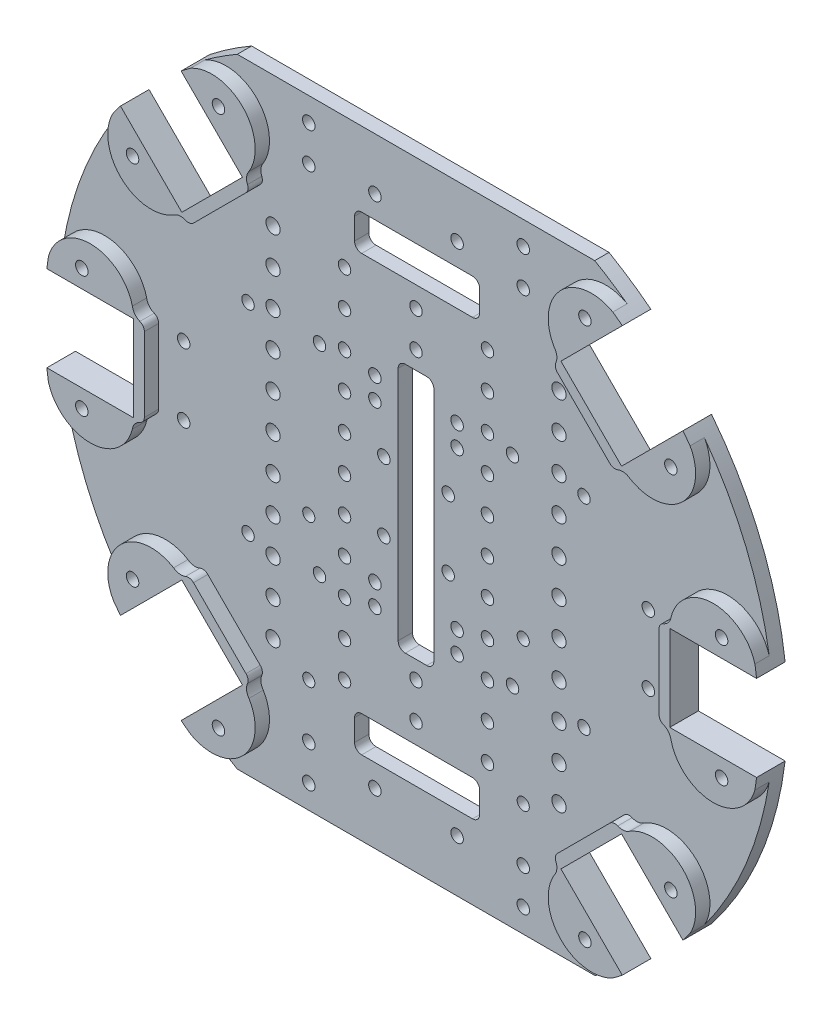
SolidWorks part; units mm, degrees
ref_plane "Front Plane" through (0, 0, 0) normal (0, 0, 1) x (1, 0, 0)
ref_plane "Top Plane" through (0, 0, 0) normal (0, 1, 0) x (1, 0, 0)
ref_plane "Right Plane" through (0, 0, 0) normal (1, 0, 0) x (0, 0, -1)
sketch "Sketch1" plane through (0, 0, 0) normal (0, 0, 1) x (1, 0, 0)
  line L0 (0, 0) -> (0, 100) construction
  line L5 (44.5477, 61.5183) -> (61.7144, 78.685)
  line L6 (44.5477, 61.5183) -> (61.5183, 44.5477)
  line L7 (-12, 75) -> (12, 75) construction
  line L8 (-12, 75) -> (-12, 99.2774) construction
  line L9 (12, 75) -> (12, 99.2774) construction
  line L10 (-17, 89.5) -> (17, 89.5) construction
  line L11 (61.5183, 44.5477) -> (78.685, 61.7144)
  line L12 (75, 12) -> (99.2774, 12)
  line L13 (75, 12) -> (75, -12)
  line L14 (75, -12) -> (99.2774, -12)
  line L15 (61.5183, -44.5477) -> (78.685, -61.7144)
  line L16 (61.5183, -44.5477) -> (44.5477, -61.5183)
  line L17 (44.5477, -61.5183) -> (61.7144, -78.685)
  line L18 (12, -75) -> (12, -99.2774) construction
  line L19 (12, -75) -> (-12, -75) construction
  line L20 (-12, -75) -> (-12, -99.2774) construction
  line L21 (-44.5477, -61.5183) -> (-61.7144, -78.685)
  line L22 (-44.5477, -61.5183) -> (-61.5183, -44.5477)
  line L23 (-61.5183, -44.5477) -> (-78.685, -61.7144)
  line L24 (-75, -12) -> (-99.2774, -12)
  line L25 (-75, -12) -> (-75, 12)
  line L26 (-75, 12) -> (-99.2774, 12)
  line L27 (-61.5183, 44.5477) -> (-78.685, 61.7144)
  line L28 (-61.5183, 44.5477) -> (-44.5477, 61.5183)
  line L29 (-44.5477, 61.5183) -> (-61.7144, 78.685)
  circle A1 centre (0, 0) radius 100
  circle A2 centre (-17, 89.5) radius 1.75 construction
  circle A3 centre (17, 89.5) radius 1.75 construction
  circle A4 centre (51.2652, 75.3069) radius 1.75
  circle A5 centre (75.3069, 51.2652) radius 1.75
  circle A6 centre (89.5, 17) radius 1.75
  circle A7 centre (89.5, -17) radius 1.75
  circle A8 centre (75.3069, -51.2652) radius 1.75
  circle A9 centre (51.2652, -75.3069) radius 1.75
  circle A10 centre (17, -89.5) radius 1.75 construction
  circle A11 centre (-17, -89.5) radius 1.75 construction
  circle A12 centre (-51.2652, -75.3069) radius 1.75
  circle A13 centre (-75.3069, -51.2652) radius 1.75
  circle A14 centre (-89.5, -17) radius 1.75
  circle A15 centre (-89.5, 17) radius 1.75
  circle A16 centre (-75.3069, 51.2652) radius 1.75
  circle A17 centre (-51.2652, 75.3069) radius 1.75
  point P2 (0, 89.5)
  point P4 (0, 75)
  point P12 (0, 75)
  point P19 (0, 89.5)
  dimension "150" = 200
  dimension "D7" = 3.5
  dimension "D2" = 25
  dimension "D3" = 8
  dimension "D4" = 24
  dimension "D5" = 14.5
  dimension "D6" = 34
extrude "Boss-Extrude1" add sketch "Sketch1" along normal blind 4 contours L12 A1 L11 L6 L5 L29 L28 L27 L26 L25 L24 L23 L22 L21 L17 L16 L15 L14 L13 A15 A14 A9 A8 A5 A4 A6 A7 A12 A13 A16 A17
sketch "Sketch2" plane through (0, 0, 4) normal (0, 0, 1) x (1, 0, 0)
  line L0 (0, 35) -> (0, -35) construction
  line L1 (-35, 35) -> (35, 35) construction
  line L2 (-35, 35) -> (-35, -35) construction
  line L3 (-35, -35) -> (35, -35) construction
  line L4 (35, 35) -> (35, -35) construction
  line L5 (-35, 35) -> (35, -35) construction
  line L6 (-35, -35) -> (35, 35) construction
  line L7 (0, 35) -> (0, 80)
  line L8 (-30, -15) -> (30, -15) construction
  line L9 (-30, -15) -> (-30, -55) construction
  line L10 (-30, -55) -> (30, -55) construction
  line L11 (30, -15) -> (30, -55) construction
  line L12 (-30, -15) -> (30, -55) construction
  line L13 (-30, -55) -> (30, -15) construction
  line L14 (-30, 80) -> (30, 80)
  line L15 (0, -55) -> (0, -80)
  line L16 (30, -80) -> (-30, -80)
  line L17 (0, 0) -> (-40, 0) construction
  line L18 (0, 0) -> (40, 0) construction
  line L19 (0, 10) -> (-40, 10)
  line L20 (0, 10) -> (40, 10)
  line L21 (0, 20) -> (-40, 20)
  line L22 (0, 20) -> (40, 20)
  line L23 (0, 30) -> (-40, 30)
  line L24 (0, 30) -> (40, 30)
  line L25 (0, 40) -> (-40, 40)
  line L26 (0, 40) -> (40, 40)
  line L27 (0, 50) -> (-40, 50)
  line L28 (0, 50) -> (40, 50)
  line L29 (0, -10) -> (40, -10)
  line L30 (0, -10) -> (-40, -10)
  line L31 (0, -20) -> (40, -20)
  line L32 (0, -20) -> (-40, -20)
  line L33 (0, -30) -> (40, -30)
  line L34 (0, -30) -> (-40, -30)
  line L35 (0, -40) -> (40, -40)
  line L36 (0, -40) -> (-40, -40)
  line L37 (0, -50) -> (40, -50)
  line L38 (0, -50) -> (-40, -50)
  line L39 (30, -70) -> (-30, -70)
  line L40 (-30, 70) -> (30, 70)
  circle A0 centre (0, 0) radius 100
  circle A1 centre (-30, -55) radius 1.7
  circle A2 centre (-30, -15) radius 1.7
  circle A3 centre (30, -55) radius 1.7
  circle A4 centre (30, -15) radius 1.7
  circle A5 centre (-30, 80) radius 1.75
  circle A6 centre (30, 80) radius 1.75
  circle A7 centre (-30, -80) radius 1.75
  circle A8 centre (30, -80) radius 1.75
  circle A9 centre (-40, 0) radius 2
  circle A10 centre (-20, 0) radius 1.75
  circle A11 centre (0, 0) radius 1.75
  circle A12 centre (40, 0) radius 2
  circle A13 centre (20, 0) radius 1.75
  circle A14 centre (20, 10) radius 1.75
  circle A15 centre (40, 10) radius 2
  circle A16 centre (-20, 10) radius 1.75
  circle A17 centre (-40, 10) radius 2
  circle A18 centre (0, 10) radius 1.75
  circle A19 centre (20, 20) radius 1.75
  circle A20 centre (40, 20) radius 2
  circle A21 centre (-20, 20) radius 1.75
  circle A22 centre (-40, 20) radius 2
  circle A23 centre (0, 20) radius 1.75
  circle A24 centre (20, 30) radius 1.75
  circle A25 centre (40, 30) radius 2
  circle A26 centre (-20, 30) radius 1.75
  circle A27 centre (-40, 30) radius 2
  circle A28 centre (0, 30) radius 1.75
  circle A29 centre (20, 40) radius 1.75
  circle A30 centre (40, 40) radius 2
  circle A31 centre (-20, 40) radius 1.75
  circle A32 centre (-40, 40) radius 2
  circle A33 centre (0, 40) radius 1.75
  circle A34 centre (20, 50) radius 1.75
  circle A35 centre (40, 50) radius 2
  circle A36 centre (-20, 50) radius 1.75
  circle A37 centre (-40, 50) radius 2
  circle A38 centre (0, 50) radius 1.75
  circle A39 centre (40, -10) radius 2
  circle A40 centre (0, -10) radius 1.75
  circle A41 centre (20, -10) radius 1.75
  circle A42 centre (-20, -10) radius 1.75
  circle A43 centre (-40, -10) radius 2
  circle A44 centre (40, -20) radius 2
  circle A45 centre (0, -20) radius 1.75
  circle A46 centre (20, -20) radius 1.75
  circle A47 centre (-20, -20) radius 1.75
  circle A48 centre (-40, -20) radius 2
  circle A49 centre (40, -30) radius 2
  circle A50 centre (0, -30) radius 1.75
  circle A51 centre (20, -30) radius 1.75
  circle A52 centre (-20, -30) radius 1.75
  circle A53 centre (-40, -30) radius 2
  circle A54 centre (40, -40) radius 2
  circle A55 centre (0, -40) radius 1.75
  circle A56 centre (20, -40) radius 1.75
  circle A57 centre (-20, -40) radius 1.75
  circle A58 centre (-40, -40) radius 2
  circle A59 centre (40, -50) radius 2
  circle A60 centre (0, -50) radius 1.75
  circle A61 centre (20, -50) radius 1.75
  circle A62 centre (-20, -50) radius 1.75
  circle A63 centre (-40, -50) radius 2
  circle A64 centre (30, -70) radius 1.75
  circle A65 centre (-30, -70) radius 1.75
  circle A66 centre (-30, 70) radius 1.75
  circle A67 centre (30, 70) radius 1.75
  point P10 (0, 0)
  point P23 (0, 80)
  point P30 (0, -80)
  dimension "D1" = 200
  dimension "D6" = 3.4
  dimension "D9" = 3.5
  dimension "D10" = 3.5
  dimension "D13" = 3.5
  dimension "D14" = 3.5
  dimension "D16" = 4
  dimension "D17" = 3.5
  dimension "D18" = 3.5
  dimension "D2" = 70
  dimension "D3" = 70
  dimension "D4" = 40
  dimension "D5" = 60
  dimension "D7" = 45
  dimension "D8" = 60
  dimension "D11" = 25
  dimension "D12" = 60
  dimension "D15" = 40
  dimension "D19" = 6
  dimension "D20" = 6
  dimension "D21" = 2
  dimension "D22" = 2
extrude "Cut-Extrude1" cut sketch "Sketch2" against normal blind 10
sketch "Sketch3" plane through (0, 0, 4) normal (0, 0, 1) x (1, 0, 0)
  line L0 (-78.685, 61.7144) -> (-61.5183, 44.5477)
  line L1 (-61.5183, 44.5477) -> (-44.5477, 61.5183)
  line L2 (-44.5477, 61.5183) -> (-61.7144, 78.685)
  line L3 (-58.255, 43.5684) -> (-43.5684, 58.255)
  line L4 (-53.033, 53.033) -> (-50.9117, 50.9117)
  line L5 (-10.385, 72) -> (10.385, 72)
  line L6 (-12, 75) -> (12, 75)
  line L7 (-12, 99.2774) -> (-12, 75)
  line L8 (12, 75) -> (12, 99.2774)
  line L9 (43.5684, 58.255) -> (58.255, 43.5684)
  line L10 (44.5477, 61.5183) -> (61.5183, 44.5477)
  line L11 (61.7144, 78.685) -> (44.5477, 61.5183)
  line L12 (61.5183, 44.5477) -> (78.685, 61.7144)
  line L13 (72, 10.385) -> (72, -10.385)
  line L14 (75, 12) -> (75, -12)
  line L15 (99.2774, 12) -> (75, 12)
  line L16 (75, -12) -> (99.2774, -12)
  line L17 (58.255, -43.5684) -> (43.5684, -58.255)
  line L18 (61.5183, -44.5477) -> (44.5477, -61.5183)
  line L19 (78.685, -61.7144) -> (61.5183, -44.5477)
  line L20 (44.5477, -61.5183) -> (61.7144, -78.685)
  line L21 (10.385, -72) -> (-10.385, -72)
  line L22 (12, -75) -> (-12, -75)
  line L23 (12, -99.2774) -> (12, -75)
  line L24 (-12, -75) -> (-12, -99.2774)
  line L25 (-43.5684, -58.255) -> (-58.255, -43.5684)
  line L26 (-44.5477, -61.5183) -> (-61.5183, -44.5477)
  line L27 (-61.7144, -78.685) -> (-44.5477, -61.5183)
  line L28 (-61.5183, -44.5477) -> (-78.685, -61.7144)
  line L29 (-72, -10.385) -> (-72, 10.385)
  line L30 (-75, -12) -> (-75, 12)
  line L31 (-99.2774, -12) -> (-75, -12)
  line L32 (-75, 12) -> (-99.2774, 12)
  arc A1 (-12.2421, 73.2574) -> (-10.385, 72) centre (-10.385, 74) ccw
  circle A2 centre (0, 0) radius 100
  arc A3 (-61.5183, 44.5477) -> (-78.685, 61.7144) centre (-70.1016, 53.1311) cw
  arc A4 (-61.7144, 78.685) -> (-44.5477, 61.5183) centre (-53.1311, 70.1016) cw
  circle A5 centre (-51.2652, 75.3069) radius 1.75
  circle A6 centre (-75.3069, 51.2652) radius 1.75
  arc A7 (-43.1444, 60.4573) -> (-42.7452, 63.8182) centre (-40.0316, 61.7918) cw
  arc A8 (-60.4573, 43.1444) -> (-63.8182, 42.7452) centre (-61.7918, 40.0316) ccw
  arc A9 (-60.4573, 43.1444) -> (-58.255, 43.5684) centre (-59.6692, 44.9826) ccw
  arc A10 (-43.1444, 60.4573) -> (-43.5684, 58.255) centre (-44.9826, 59.6692) cw
  arc A11 (-12.2421, 73.2574) -> (-14.9009, 75.3517) centre (-15.3867, 72) ccw
  arc A12 (-12, 75) -> (-12, 99.2774) centre (-12, 87.1387) cw
  circle A13 centre (-17, 89.5) radius 1.75
  circle A14 centre (17, 89.5) radius 1.75
  arc A15 (12, 99.2774) -> (12, 75) centre (12, 87.1387) cw
  arc A16 (12.2421, 73.2574) -> (14.9009, 75.3517) centre (15.3867, 72) cw
  arc A17 (12.2421, 73.2574) -> (10.385, 72) centre (10.385, 74) cw
  arc A18 (43.1444, 60.4573) -> (43.5684, 58.255) centre (44.9826, 59.6692) ccw
  arc A19 (43.1444, 60.4573) -> (42.7452, 63.8182) centre (40.0316, 61.7918) ccw
  arc A20 (44.5477, 61.5183) -> (61.7144, 78.685) centre (53.1311, 70.1016) cw
  circle A21 centre (51.2652, 75.3069) radius 1.75
  circle A22 centre (75.3069, 51.2652) radius 1.75
  arc A23 (78.685, 61.7144) -> (61.5183, 44.5477) centre (70.1016, 53.1311) cw
  arc A24 (60.4573, 43.1444) -> (63.8182, 42.7452) centre (61.7918, 40.0316) cw
  arc A25 (60.4573, 43.1444) -> (58.255, 43.5684) centre (59.6692, 44.9826) cw
  arc A26 (73.2574, 12.2421) -> (72, 10.385) centre (74, 10.385) ccw
  arc A27 (73.2574, 12.2421) -> (75.3517, 14.9009) centre (72, 15.3867) ccw
  arc A28 (75, 12) -> (99.2774, 12) centre (87.1387, 12) cw
  circle A29 centre (89.5, 17) radius 1.75
  circle A30 centre (89.5, -17) radius 1.75
  arc A31 (99.2774, -12) -> (75, -12) centre (87.1387, -12) cw
  arc A32 (73.2574, -12.2421) -> (75.3517, -14.9009) centre (72, -15.3867) cw
  arc A33 (73.2574, -12.2421) -> (72, -10.385) centre (74, -10.385) cw
  arc A34 (60.4573, -43.1444) -> (58.255, -43.5684) centre (59.6692, -44.9826) ccw
  arc A35 (60.4573, -43.1444) -> (63.8182, -42.7452) centre (61.7918, -40.0316) ccw
  arc A36 (61.5183, -44.5477) -> (78.685, -61.7144) centre (70.1016, -53.1311) cw
  circle A37 centre (75.3069, -51.2652) radius 1.75
  circle A38 centre (51.2652, -75.3069) radius 1.75
  arc A39 (61.7144, -78.685) -> (44.5477, -61.5183) centre (53.1311, -70.1016) cw
  arc A40 (43.1444, -60.4573) -> (42.7452, -63.8182) centre (40.0316, -61.7918) cw
  arc A41 (43.1444, -60.4573) -> (43.5684, -58.255) centre (44.9826, -59.6692) cw
  arc A42 (12.2421, -73.2574) -> (10.385, -72) centre (10.385, -74) ccw
  arc A43 (12.2421, -73.2574) -> (14.9009, -75.3517) centre (15.3867, -72) ccw
  arc A44 (12, -75) -> (12, -99.2774) centre (12, -87.1387) cw
  circle A45 centre (17, -89.5) radius 1.75
  circle A46 centre (-17, -89.5) radius 1.75
  arc A47 (-12, -99.2774) -> (-12, -75) centre (-12, -87.1387) cw
  arc A48 (-12.2421, -73.2574) -> (-14.9009, -75.3517) centre (-15.3867, -72) cw
  arc A49 (-12.2421, -73.2574) -> (-10.385, -72) centre (-10.385, -74) cw
  arc A50 (-43.1444, -60.4573) -> (-43.5684, -58.255) centre (-44.9826, -59.6692) ccw
  arc A51 (-43.1444, -60.4573) -> (-42.7452, -63.8182) centre (-40.0316, -61.7918) ccw
  arc A52 (-44.5477, -61.5183) -> (-61.7144, -78.685) centre (-53.1311, -70.1016) cw
  circle A53 centre (-51.2652, -75.3069) radius 1.75
  circle A54 centre (-75.3069, -51.2652) radius 1.75
  arc A55 (-78.685, -61.7144) -> (-61.5183, -44.5477) centre (-70.1016, -53.1311) cw
  arc A56 (-60.4573, -43.1444) -> (-63.8182, -42.7452) centre (-61.7918, -40.0316) cw
  arc A57 (-60.4573, -43.1444) -> (-58.255, -43.5684) centre (-59.6692, -44.9826) cw
  arc A58 (-73.2574, -12.2421) -> (-72, -10.385) centre (-74, -10.385) ccw
  arc A59 (-73.2574, -12.2421) -> (-75.3517, -14.9009) centre (-72, -15.3867) ccw
  arc A60 (-75, -12) -> (-99.2774, -12) centre (-87.1387, -12) cw
  circle A61 centre (-89.5, -17) radius 1.75
  circle A62 centre (-89.5, 17) radius 1.75
  arc A63 (-99.2774, 12) -> (-75, 12) centre (-87.1387, 12) cw
  arc A64 (-73.2574, 12.2421) -> (-75.3517, 14.9009) centre (-72, 15.3867) cw
  arc A65 (-73.2574, 12.2421) -> (-72, 10.385) centre (-74, 10.385) cw
  point P29 (-59.397, 42.4264)
  point P32 (-42.4264, 59.397)
  dimension "D2" = 2
  dimension "D1" = 2
  dimension "D3" = 8
extrude "Boss-Extrude2" add sketch "Sketch3" along normal blind 4 contours A39 A40 A2 L20 A38 | A41 A40 A39 L18 A36 A35 A34 L17 | A36 L19 A2 A35 A37 | A31 A32 A2 L16 A30 | A33 A32 A31 L14 A28 A27 A26 L13 | A28 L15 A2 A27 A29 | A23 A24 A2 L12 A22 | A25 A24 A23 L10 A20 A19 A18 L9 | A20 L11 A2 A19 A21 | A4 A7 A2 L2 A5 | A10 A7 A4 L1 L4 L3 | A8 A9 L3 L4 L1 A3 | A8 A3 L0 A2 A6 | A63 A64 A2 L32 A62 | A65 A64 A63 L30 A60 A59 A58 L29 | A60 L31 A2 A59 A61 | A55 A56 A2 L28 A54 | A57 A56 A55 L26 A52 A51 A50 L25 | A52 L27 A2 A51 A53
sketch "Sketch4" plane through (0, 0, 0) normal (0, 0, -1) x (-1, 0, 0)
  line L0 (-11.5, 72) -> (-11.5, 28)
  line L1 (-11.5, 22) -> (11.5, 22) construction
  line L2 (-11.5, 22) -> (-11.5, -22) construction
  line L3 (-11.5, -22) -> (11.5, -22) construction
  line L4 (11.5, 22) -> (11.5, -22) construction
  line L5 (-11.5, 22) -> (11.5, -22) construction
  line L6 (-11.5, -22) -> (11.5, 22) construction
  line L7 (-11.5, 72) -> (11.5, 72)
  line L8 (11.5, 72) -> (11.5, 28)
  line L9 (-11.5, 28) -> (11.5, 28)
  line L10 (-11.5, 22) -> (-11.5, -22)
  line L11 (-11.5, 22) -> (11.5, 22)
  line L12 (11.5, 22) -> (11.5, -22)
  line L13 (-11.5, -22) -> (11.5, -22)
  line L14 (-11.5, -28) -> (-11.5, -72)
  line L15 (-11.5, -28) -> (11.5, -28)
  line L16 (11.5, -28) -> (11.5, -72)
  line L17 (-11.5, -72) -> (11.5, -72)
  line L18 (0, 0) -> (100, 0)
  line L19 (-47, 28) -> (-47, -28)
  line L20 (35, 28) -> (55, 28) construction
  line L21 (35, 28) -> (35, -28) construction
  line L22 (35, -28) -> (55, -28) construction
  line L23 (55, 28) -> (55, -28) construction
  line L24 (35, 28) -> (55, -28) construction
  line L25 (35, -28) -> (55, 28) construction
  line L26 (-47, 28) -> (-27, 28)
  line L27 (-27, 28) -> (-27, -28)
  line L28 (-47, -28) -> (-27, -28)
  line L29 (0, 22) -> (0, -22)
  line L30 (47, 28) -> (27, 28)
  line L31 (27, 28) -> (27, -28)
  line L32 (47, -28) -> (27, -28)
  line L33 (47, 28) -> (47, -28)
  circle A0 centre (0, 0) radius 100
  circle A1 centre (-11.5, 22) radius 1.75
  circle A2 centre (11.5, 22) radius 1.75
  circle A3 centre (11.5, -22) radius 1.75
  circle A4 centre (-11.5, -22) radius 1.75
  circle A5 centre (11.5, 72) radius 1.75
  circle A6 centre (-11.5, 72) radius 1.75
  circle A7 centre (-11.5, 28) radius 1.75
  circle A8 centre (11.5, 28) radius 1.75
  circle A9 centre (11.5, 22) radius 1.75
  circle A10 centre (-11.5, 22) radius 1.75
  circle A11 centre (-11.5, -22) radius 1.75
  circle A12 centre (11.5, -22) radius 1.75
  circle A13 centre (11.5, -28) radius 1.75
  circle A14 centre (-11.5, -28) radius 1.75
  circle A15 centre (-11.5, -72) radius 1.75
  circle A16 centre (11.5, -72) radius 1.75
  circle A17 centre (35, 28) radius 1.75 construction
  circle A18 centre (55, 28) radius 1.75 construction
  circle A19 centre (55, -28) radius 1.75 construction
  circle A20 centre (35, -28) radius 1.75 construction
  circle A21 centre (-47, 28) radius 1.75
  circle A22 centre (-27, 28) radius 1.75
  circle A23 centre (-47, -28) radius 1.75
  circle A24 centre (-27, -28) radius 1.75
  circle A25 centre (47, 28) radius 1.75
  circle A26 centre (27, 28) radius 1.75
  circle A27 centre (47, -28) radius 1.75
  circle A28 centre (27, -28) radius 1.75
  point P11 (45, 0)
  point P13 (45, 0)
  dimension "D3" = 3.5
  dimension "D9" = 3.5
  dimension "D1" = 44
  dimension "D2" = 23
  dimension "D6" = 45
  dimension "D7" = 56
  dimension "D8" = 20
  dimension "D4" = 2
  dimension "D5" = 2
  dimension "D10" = 2
extrude "Cut-Extrude2" cut sketch "Sketch4" against normal blind 10 contours L8 A5 L7 | L7 A5 L8 | L7 A6 L0 | L0 A6 L7 | L0 A7 L9 | L9 A7 L0 | L9 A8 L8 | L8 A8 L9 | L12 A2 L11 | L11 A2 L12 | L11 A1 L10 | L10 A1 L11 | L12 A3 L13 | L13 A3 L12 | L13 A4 L10 | L10 A4 L13 | L15 A14 L14 | L14 A14 L15 | L15 A13 L16 | L16 A13 L15 | L14 A15 L17 | L17 A15 L14 | L17 A16 L16 | L16 A16 L17 | L26 A21 L19 | L19 A21 L26 | L26 A22 L27 | L27 A22 L26 | L28 A24 L27 | L27 A24 L28 | L19 A23 L28 | L28 A23 L19 | A25 L30 L33 | A25 L33 L30 | A26 L30 L31 | A26 L31 L30 | A27 L33 L32 | A27 L32 L33 | A28 L32 L31 | A28 L31 L32
sketch "Sketch5" plane through (0, 0, 0) normal (0, 0, -1) x (-1, 0, 0)
  line L0 (9, 9.6) -> (9, -9.6) construction
  line L1 (-3, 35) -> (3, 35)
  line L2 (-5, 33) -> (-5, -33)
  line L3 (-3, -35) -> (3, -35)
  line L4 (5, 33) -> (5, -33)
  line L5 (-5, 35) -> (5, -35) construction
  line L6 (-5, -35) -> (5, 35) construction
  line L7 (-28, 9.6) -> (28, 9.6) construction
  line L8 (-28, 9.6) -> (-28, -9.6) construction
  line L9 (-28, -9.6) -> (28, -9.6) construction
  line L10 (28, 9.6) -> (28, -9.6) construction
  line L11 (-28, 9.6) -> (28, -9.6) construction
  line L12 (-28, -9.6) -> (28, 9.6) construction
  line L13 (9, 9.6) -> (65, 9.6) construction
  line L14 (65, 9.6) -> (65, -9.6) construction
  line L15 (9, -9.6) -> (65, -9.6) construction
  line L16 (0, 35) -> (0, 0) construction
  line L17 (0, 0) -> (5, 0) construction
  line L18 (-15.8022, -55.7522) -> (15.1978, -55.7522)
  line L19 (-17.8022, -57.7522) -> (-17.8022, -63.7522)
  line L20 (-15.8022, -65.7522) -> (15.1978, -65.7522)
  line L21 (17.1978, -57.7522) -> (17.1978, -63.7522)
  line L22 (-17.8022, -55.7522) -> (17.1978, -65.7522) construction
  line L23 (-17.8022, -65.7522) -> (17.1978, -55.7522) construction
  line L24 (-15.8022, 65.7522) -> (15.1978, 65.7522)
  line L25 (17.1978, 57.7522) -> (17.1978, 63.7522)
  line L26 (-15.8022, 55.7522) -> (15.1978, 55.7522)
  line L27 (-17.8022, 57.7522) -> (-17.8022, 63.7522)
  circle A0 centre (0, 0) radius 100
  arc A1 (17.1978, -57.7522) -> (15.1978, -55.7522) centre (15.1978, -57.7522) ccw
  arc A2 (3, -35) -> (5, -33) centre (3, -33) ccw
  arc A3 (-3, -35) -> (-5, -33) centre (-3, -33) cw
  arc A4 (3, 35) -> (5, 33) centre (3, 33) cw
  arc A5 (-3, 35) -> (-5, 33) centre (-3, 33) ccw
  circle A6 centre (-28, 9.6) radius 1.75 construction
  circle A7 centre (-28, -9.6) radius 1.75 construction
  circle A8 centre (28, 9.6) radius 1.75 construction
  circle A9 centre (28, -9.6) radius 1.75 construction
  circle A10 centre (9, 9.6) radius 1.75
  circle A11 centre (9, -9.6) radius 1.75
  circle A12 centre (65, 9.6) radius 1.75
  circle A13 centre (65, -9.6) radius 1.75
  circle A14 centre (-9, 9.6) radius 1.75
  circle A15 centre (-9, -9.6) radius 1.75
  circle A16 centre (-65, -9.6) radius 1.75
  circle A17 centre (-65, 9.6) radius 1.75
  arc A18 (17.1978, -63.7522) -> (15.1978, -65.7522) centre (15.1978, -63.7522) cw
  arc A19 (-17.8022, -63.7522) -> (-15.8022, -65.7522) centre (-15.8022, -63.7522) ccw
  arc A20 (-15.8022, -55.7522) -> (-17.8022, -57.7522) centre (-15.8022, -57.7522) ccw
  arc A21 (17.1978, 63.7522) -> (15.1978, 65.7522) centre (15.1978, 63.7522) ccw
  arc A22 (17.1978, 57.7522) -> (15.1978, 55.7522) centre (15.1978, 57.7522) cw
  arc A23 (-17.8022, 63.7522) -> (-15.8022, 65.7522) centre (-15.8022, 63.7522) cw
  arc A24 (-15.8022, 55.7522) -> (-17.8022, 57.7522) centre (-15.8022, 57.7522) cw
  point P44 (-0.3022, -60.7522)
  dimension "D3" = 2
  dimension "D6" = 3.5
  dimension "D10" = 2
  dimension "D1" = 70
  dimension "D2" = 10
  dimension "D4" = 19.2
  dimension "D5" = 56
  dimension "D8" = 10
  dimension "D9" = 35
  dimension "D7" = 2
extrude "Cut-Extrude4" cut sketch "Sketch5" against normal blind 10 contours A5 L1 A4 L4 A2 L3 A3 L2 | A14 | A10 | A11 | A15 | A17 | A16 | A12 | A13 | L19 A19 L20 A18 L21 A1 L18 A20 | L24 A21 L25 A22 L26 A24 L27 A23
sketch "Sketch6" plane through (0, 0, 4) normal (0, 0, 1) x (1, 0, 0)
  line L0 (0, 0) -> (0, -100) construction
  line L1 (-50, -86.6025) -> (50, -86.6025)
  line L2 (0, 0) -> (-100, 0) construction
  line L4 (-50, 86.6025) -> (50, 86.6025)
  circle A0 centre (0, 0) radius 100
  point P7 (0, -86.6025)
  dimension "D1" = 200
  dimension "D2" = 100
extrude "Cut-Extrude5" cut sketch "Sketch6" against normal through all contours L4 A0 | L1 A0
